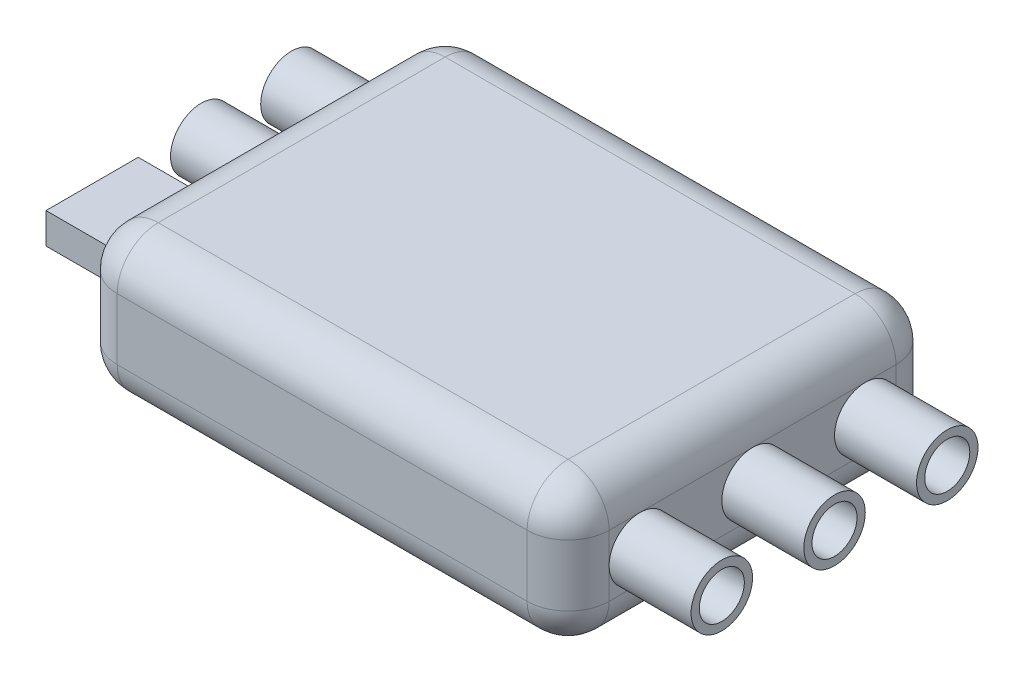
SolidWorks part; units mm, degrees
ref_plane "前视基准面" through (0, 0, 0) normal (0, 0, 1) x (1, 0, 0)
ref_plane "上视基准面" through (0, 0, 0) normal (0, 1, 0) x (1, 0, 0)
ref_plane "右视基准面" through (0, 0, 0) normal (1, 0, 0) x (0, 0, -1)
sketch "草图2" plane through (0, 0, 0) normal (0, 1, 0) x (1, 0, 0)
  line L1 (10, -9) -> (-10, -9)
  line L2 (12, -7) -> (12, 7)
  line L3 (10, 9) -> (-10, 9)
  line L4 (-12, -7) -> (-12, 7)
  line L5 (12, -9) -> (-12, 9) construction
  line L6 (12, 9) -> (-12, -9) construction
  arc A0 (-10, -9) -> (-12, -7) centre (-10, -7) cw
  arc A1 (12, 7) -> (10, 9) centre (10, 7) ccw
  arc A2 (10, -9) -> (12, -7) centre (10, -7) ccw
  arc A3 (-10, 9) -> (-12, 7) centre (-10, 7) ccw
  point P0 (0, 0)
  dimension "D3" = 2
  dimension "D1" = 24
  dimension "D2" = 18
extrude "凸台-拉伸1" add sketch "草图2" along normal blind 7
fillet "圆角1" radius 2 16 edges at (0, 0, 9) (11.4142, 0, 8.4142) (12, 0, 0) (11.4142, 0, -8.4142) (0, 0, -9) (-11.4142, 0, -8.4142) (-12, 0, 0) (-11.4142, 0, 8.4142) (-12, 7, 0) (-11.4142, 7, -8.4142) (0, 7, -9) (11.4142, 7, -8.4142) (12, 7, 0) (11.4142, 7, 8.4142) (0, 7, 9) (-11.4142, 7, 8.4142)
sketch "草图3" plane through (12, 0, 0) normal (1, 0, 0) x (0, 0, -1)
  line L0 (-7, 3.5) -> (7, 3.5) construction
  line L1 (-7, 5) -> (-7, 2) construction
  line L2 (7, 5) -> (7, 2) construction
  circle A0 centre (0, 3.5) radius 1.5
  circle A1 centre (0, 3.5) radius 1.1
  circle A2 centre (-5.5, 3.5) radius 1.5
  circle A3 centre (5.5, 3.5) radius 1.5
  circle A4 centre (-5.5, 3.5) radius 1.1
  circle A5 centre (5.5, 3.5) radius 1.1
  dimension "D1" = 3
  dimension "D2" = 0.4
extrude "凸台-拉伸2" add sketch "草图3" along normal blind 4
sketch "草图4" plane through (-12, 0, 0) normal (-1, 0, 0) x (0, 0, 1)
  line L0 (-7, 3.5) -> (7, 3.5) construction
  line L1 (-7, 5) -> (-7, 2) construction
  line L2 (7, 5) -> (7, 2) construction
  line L4 (1.9749, 4.25) -> (6.4749, 4.25)
  line L5 (1.9749, 4.25) -> (1.9749, 2.75)
  line L6 (1.9749, 2.75) -> (6.4749, 2.75)
  line L7 (6.4749, 4.25) -> (6.4749, 2.75)
  circle A0 centre (-5.5, 3.5) radius 1.5
  circle A2 centre (-5.5, 3.5) radius 1.1
  circle A4 centre (-1.1, 3.5) radius 1.5
  circle A5 centre (-1.1, 3.5) radius 1.1
  dimension "D3" = 3
  dimension "D4" = 0.4
  dimension "D1" = 4.5
  dimension "D2" = 1.5
  dimension "D5" = 4.4
extrude "凸台-拉伸3" add sketch "草图4" along normal blind 4
